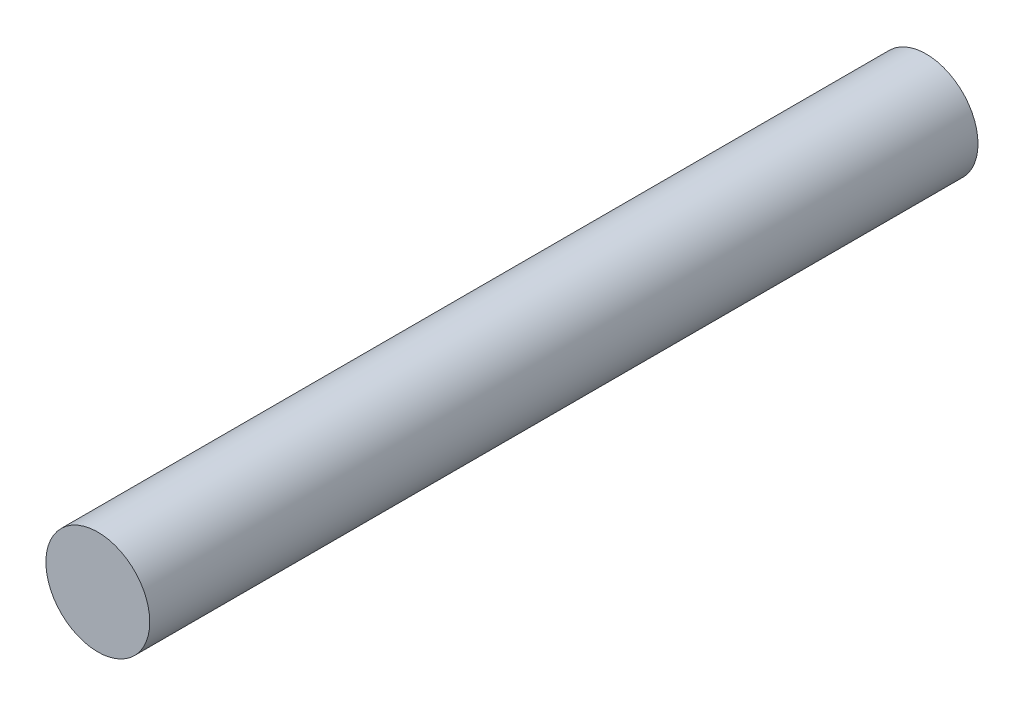
SolidWorks part; units mm, degrees
ref_plane "前视基准面" through (0, 0, 0) normal (0, 0, 1) x (1, 0, 0)
ref_plane "上视基准面" through (0, 0, 0) normal (0, 1, 0) x (1, 0, 0)
ref_plane "右视基准面" through (0, 0, 0) normal (1, 0, 0) x (0, 0, -1)
other "Configuration Table"
sketch "草图1" plane through (0, 0, 0) normal (0, 0, 1) x (1, 0, 0)
  circle A1 centre (0, 0) radius 1
  dimension "D1" = 2
extrude "凸台-拉伸1" add sketch "草图1" along normal blind 15.95
